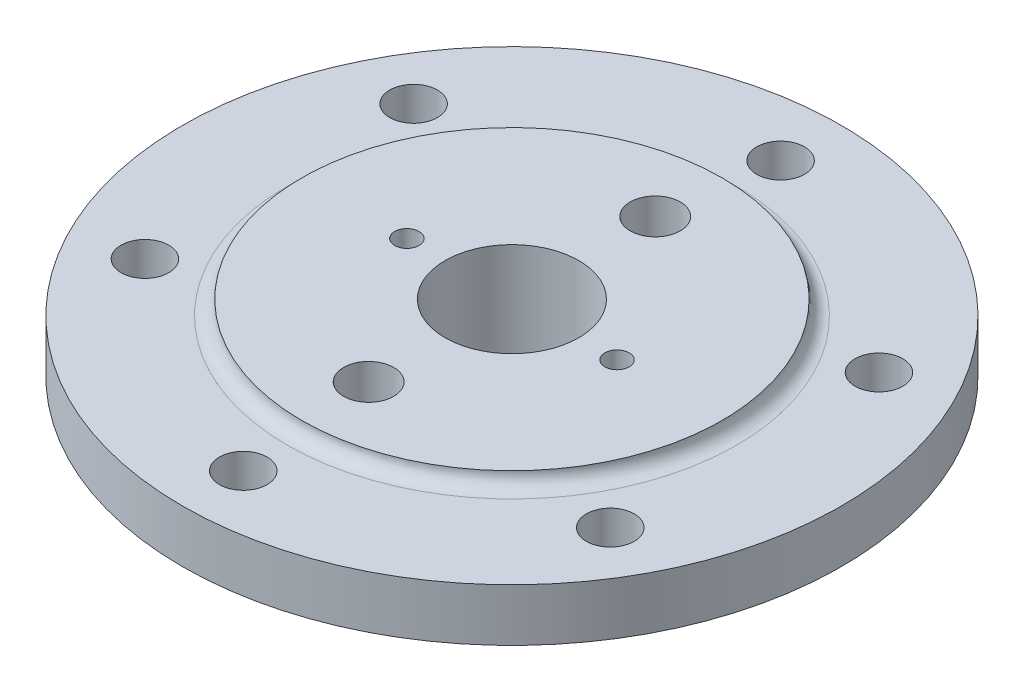
SolidWorks part; units mm, degrees
ref_plane "Front Plane" through (0, 0, 0) normal (0, 0, 1) x (1, 0, 0)
ref_plane "Top Plane" through (0, 0, 0) normal (0, 1, 0) x (1, 0, 0)
ref_plane "Right Plane" through (0, 0, 0) normal (1, 0, 0) x (0, 0, -1)
sketch "Sketch1" plane through (0, 0, 0) normal (1, 0, 0) x (0, 0, -1)
  line L0 (0, 28) -> (0, -24.8539) construction
  line L1 (-31.7753, 0) -> (55.0562, 0) construction
  line L2 (14, 0) -> (35, 0)
  line L3 (35, 0) -> (81, 47)
  line L4 (81, 47) -> (81, 53)
  line L5 (81, 53) -> (138, 53)
  line L6 (138, 53) -> (138, 75)
  line L7 (138, 75) -> (94, 75)
  line L8 (88, 81) -> (28, 81)
  line L9 (28, 81) -> (28, 39.3043)
  line L10 (28, 39.3043) -> (14, 25)
  line L11 (14, 25) -> (14, 0)
  arc A1 (94, 75) -> (88, 81) centre (94, 81) cw
  dimension "D1" = 14
  dimension "D2" = 28
  dimension "D3" = 88
  dimension "D4" = 138
  dimension "D5" = 81
  dimension "D6" = 35
  dimension "D7" = 6
  dimension "D8" = 47
  dimension "D9" = 6
  dimension "D10" = 22
  dimension "D11" = 50
revolve "Revolve1" add sketch "Sketch1" angle 360 about L0
sketch "Sketch2" plane through (0, 75, 0) normal (0, 1, 0) x (1, 0, 0)
  line L0 (0, 0) -> (0, 112.5) construction
  circle A0 centre (0, 112.5) radius 10
  circle A1 centre (97.4279, 56.25) radius 10
  circle A2 centre (97.4279, -56.25) radius 10
  circle A3 centre (0, -112.5) radius 10
  circle A4 centre (-97.4279, -56.25) radius 10
  circle A5 centre (-97.4279, 56.25) radius 10
  point P17 (0, 0)
  dimension "D1" = 20
  dimension "D2" = 112.5
  dimension "D3" = 6
extrude "Cut-Extrude1" cut sketch "Sketch2" against normal up to next
sketch "Sketch5" plane through (0, 81, 0) normal (0, 1, 0) x (1, 0, 0)
  line L0 (0, 60) -> (0, -60) construction
  point P4 (0, 60)
  point P5 (0, -60)
  dimension "D1" = 120
  dimension "D2" = 60
hole_wizard "M24 Tapped Hole1" positions "3DSketch3" profile "Sketch6" tap size "M24" standard "ISO"
sketch3d "3DSketch3"
  point P0 (0, 81, -60)
  point P3 (0, 81, 60)
cosmetic thread "Hole Thread1" parameters "D1"=66.67, "D2"=24
cosmetic thread "Hole Thread2" parameters "D1"=66.67, "D2"=24
sketch "Sketch6" plane through (0, 81, -60) normal (1, 0, 0) x (0, 0, 1)
  line L0 (0, 0) -> (0, 33.309)
  line L1 (0, 33.309) -> (10.5, 27)
  line L2 (10.5, 27) -> (10.5, 0)
  line L5 (10.5, 0) -> (0, 0)
  line L10 (0, 33.309) -> (-10.5, 27) construction
  line L11 (0, -6.35) -> (0, 107.95) construction
  dimension "Tap Drill Dia." = 21
  dimension "Tap Drill Depth" = 27
  dimension "Drill Angle" = 118
sketch "Sketch7" plane through (0, 81, 0) normal (0, 1, 0) x (1, 0, 0)
  line L0 (-44, 0) -> (44, 0) construction
  point P4 (-44, 0)
  point P5 (44, 0)
  dimension "D1" = 88
  dimension "D2" = 44
hole_wizard "M12 Tapped Hole1" positions "3DSketch4" profile "Sketch8" tap size "M12" standard "ISO"
sketch3d "3DSketch4"
  point P0 (44, 81, 0)
  point P3 (-44, 81, 0)
cosmetic thread "Hole Thread3" parameters "D1"=77.59, "D2"=12
cosmetic thread "Hole Thread4" parameters "D1"=77.59, "D2"=12
sketch "Sketch8" plane through (44, 81, 0) normal (1, 0, 0) x (0, 0, 1)
  line L0 (0, 0) -> (0, 53.0644)
  line L1 (0, 53.0644) -> (5.1, 50)
  line L2 (5.1, 50) -> (5.1, 0)
  line L5 (5.1, 0) -> (0, 0)
  line L10 (0, 53.0644) -> (-5.1, 50) construction
  line L11 (0, -6.35) -> (0, 107.95) construction
  dimension "Tap Drill Dia." = 10.2
  dimension "Tap Drill Depth" = 50
  dimension "Drill Angle" = 118
